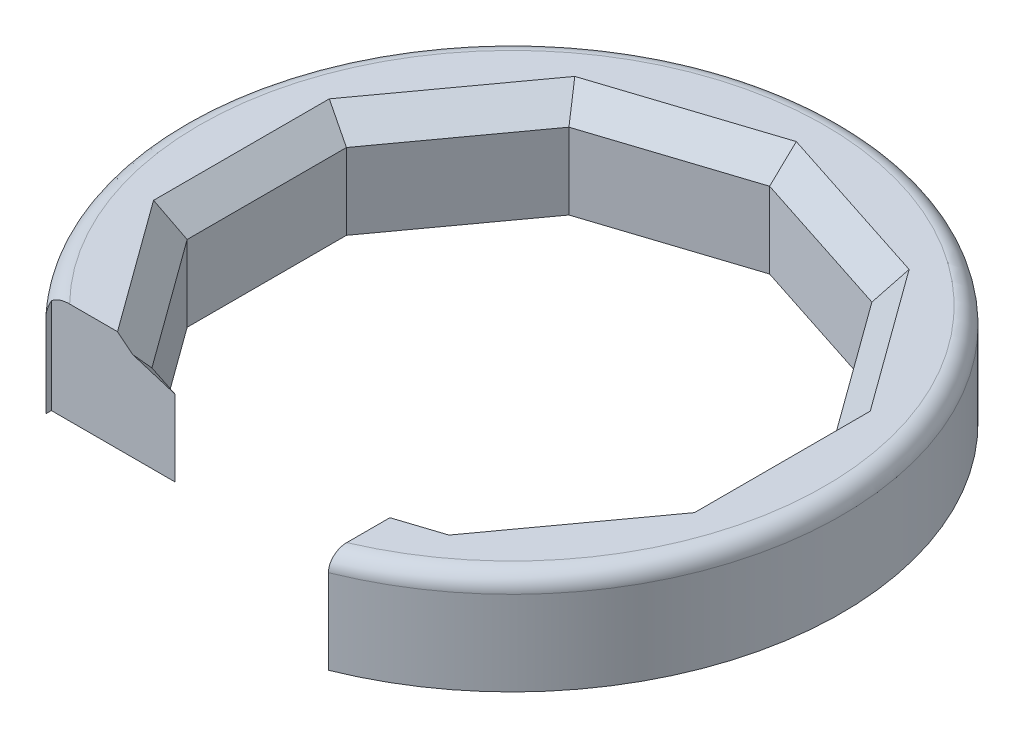
SolidWorks part; units mm, degrees
ref_plane "Front Plane" through (0, 0, 0) normal (0, 0, 1) x (1, 0, 0)
ref_plane "Top Plane" through (0, 0, 0) normal (0, 1, 0) x (1, 0, 0)
ref_plane "Right Plane" through (0, 0, 0) normal (1, 0, 0) x (0, 0, -1)
sketch "Sketch1" plane through (0, 0, 0) normal (0, 1, 0) x (1, 0, 0)
  line L1 (17.923, 24.6689) -> (0, 30.4924)
  line L2 (0, 30.4924) -> (-17.923, 24.6689)
  line L3 (-17.923, 24.6689) -> (-29, 9.4227)
  line L4 (-29, 9.4227) -> (-29, -9.4227)
  line L5 (-29, -9.4227) -> (-17.923, -24.6689)
  line L6 (-17.923, -24.6689) -> (0, -30.4924)
  line L7 (0, -30.4924) -> (17.923, -24.6689)
  line L8 (17.923, -24.6689) -> (29, -9.4227)
  line L9 (29, -9.4227) -> (29, 9.4227)
  line L10 (29, 9.4227) -> (17.923, 24.6689)
  circle A0 centre (0, 0) radius 39
  circle A1 centre (0, 0) radius 29 construction
  dimension "D1" = 78
  dimension "D2" = 10
extrude "Boss-Extrude1" add sketch "Sketch1" along normal blind 12
fillet "Fillet1" radius 2 1 edges at (0, 12, 39)
chamfer "Chamfer1" distance 3 angle 45 10 edges at (-8.9615, 12, 27.5806) (8.9615, 12, 27.5806) (23.4615, 12, 17.0458) (29, 12, 0) (23.4615, 12, -17.0458) (8.9615, 12, -27.5806) (-8.9615, 12, -27.5806) (-23.4615, 12, -17.0458) (-29, 12, 0) (-23.4615, 12, 17.0458)
sketch "Sketch2" plane through (0, 0, 0) normal (0, 1, 0) x (1, 0, 0)
  line L0 (0, 0) -> (0, -68.9868) construction
  line L1 (14.5, -68.9868) -> (-28.5, -68.9868)
  line L2 (14.5, -68.9868) -> (14.5, -25.9868)
  line L3 (14.5, -25.9868) -> (-28.5, -25.9868)
  line L4 (-28.5, -68.9868) -> (-28.5, -25.9868)
  line L5 (14.5, -68.9868) -> (-28.5, -25.9868) construction
  line L6 (14.5, -25.9868) -> (-28.5, -68.9868) construction
  line L7 (0, 0) -> (-7, -47.4868) construction
  point P0 (-7, -47.4868)
  point P8 (-4.5995, -47.7791)
  dimension "D1" = 7
  dimension "D2" = 48
  dimension "D3" = 43
  dimension "D4" = 43
extrude "Cut-Extrude2" cut sketch "Sketch2" along normal through all
